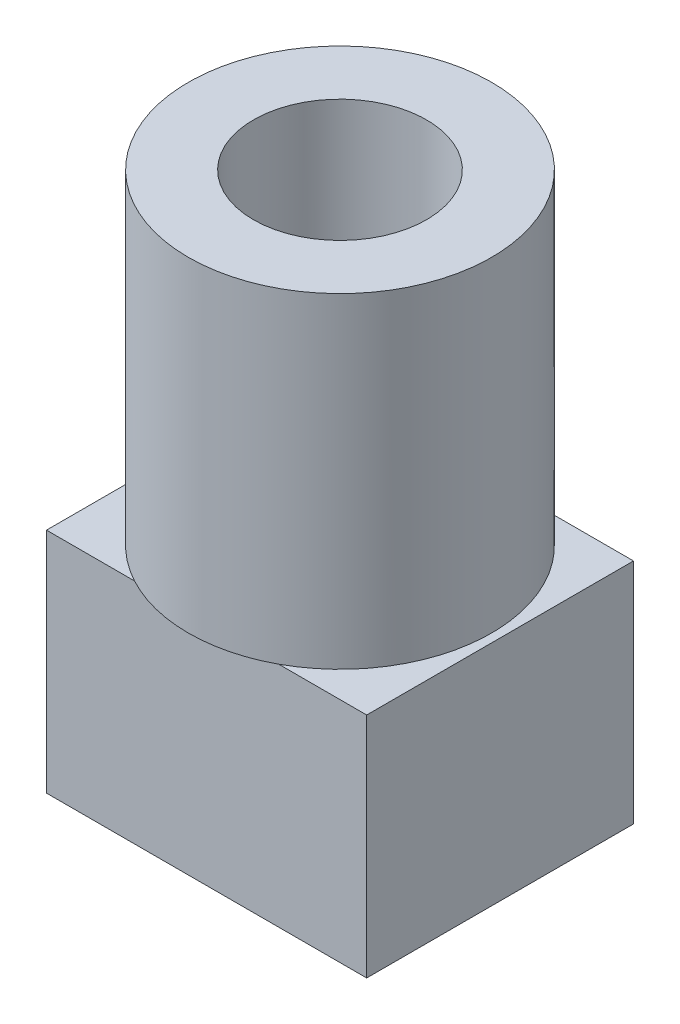
SolidWorks part; units mm, degrees
ref_plane "Front Plane" through (0, 0, 0) normal (0, 0, 1) x (1, 0, 0)
ref_plane "Top Plane" through (0, 0, 0) normal (0, 1, 0) x (1, 0, 0)
ref_plane "Right Plane" through (0, 0, 0) normal (1, 0, 0) x (0, 0, -1)
sketch "Sketch2" plane through (0, 0, 0) normal (0, 1, 0) x (1, 0, 0)
  line L1 (0, 0) -> (9.84, 0)
  line L2 (0, 0) -> (0, 8.2)
  line L3 (0, 8.2) -> (9.84, 8.2)
  line L4 (9.84, 0) -> (9.84, 8.2)
  dimension "D1" = 8.2
  dimension "D2" = 9.84
extrude "Boss-Extrude1" add sketch "Sketch2" along normal blind 7
sketch "Sketch3" plane through (0, 7, 0) normal (0, 1, 0) x (1, 0, 0)
  line L0 (9.84, 8.2) -> (0, 8.2) construction
  line L1 (2, 6.2) -> (7.84, 6.2)
  line L2 (2, 6.2) -> (2, 2)
  line L3 (2, 2) -> (7.84, 2)
  line L4 (7.84, 6.2) -> (7.84, 2)
  line L5 (0, 0) -> (9.84, 0) construction
  line L6 (0, 8.2) -> (0, 0) construction
  line L7 (9.84, 0) -> (9.84, 8.2) construction
  dimension "D1" = 2
  dimension "D2" = 2
  dimension "D3" = 2
  dimension "D4" = 2
extrude "Cut-Extrude1" cut sketch "Sketch3" against normal through all
sketch "Sketch4" plane through (0, 7, 0) normal (0, 1, 0) x (1, 0, 0)
  line L0 (4.92, 8.2) -> (4.92, 0) construction
  line L1 (9.84, 8.2) -> (0, 8.2) construction
  line L2 (0, 0) -> (9.84, 0) construction
  line L3 (9.84, 0) -> (9.84, 8.2) construction
  line L4 (0, 4.1) -> (9.84, 4.1) construction
  line L5 (0, 8.2) -> (0, 0) construction
  circle A0 centre (4.92, 4.1) radius 4.66
  dimension "D1" = 9.32
extrude "Boss-Extrude2" add sketch "Sketch4" along normal blind 10
sketch "Sketch5" plane through (0, 17, 0) normal (0, 1, 0) x (1, 0, 0)
  line L0 (0, 4.1) -> (9.84, 4.1) construction
  line L1 (0, 8.2) -> (0, 0) construction
  line L2 (9.84, 0) -> (9.84, 8.2) construction
  line L3 (4.92, 4.1) -> (4.92, 8.76) construction
  line L4 (4.92, 8.76) -> (4.92, -0.56) construction
  circle A0 centre (4.92, 4.1) radius 4.66 construction
  circle A1 centre (4.92, 4.1) radius 2.66
  dimension "D1" = 2
extrude "Cut-Extrude2" cut sketch "Sketch5" against normal blind 10
